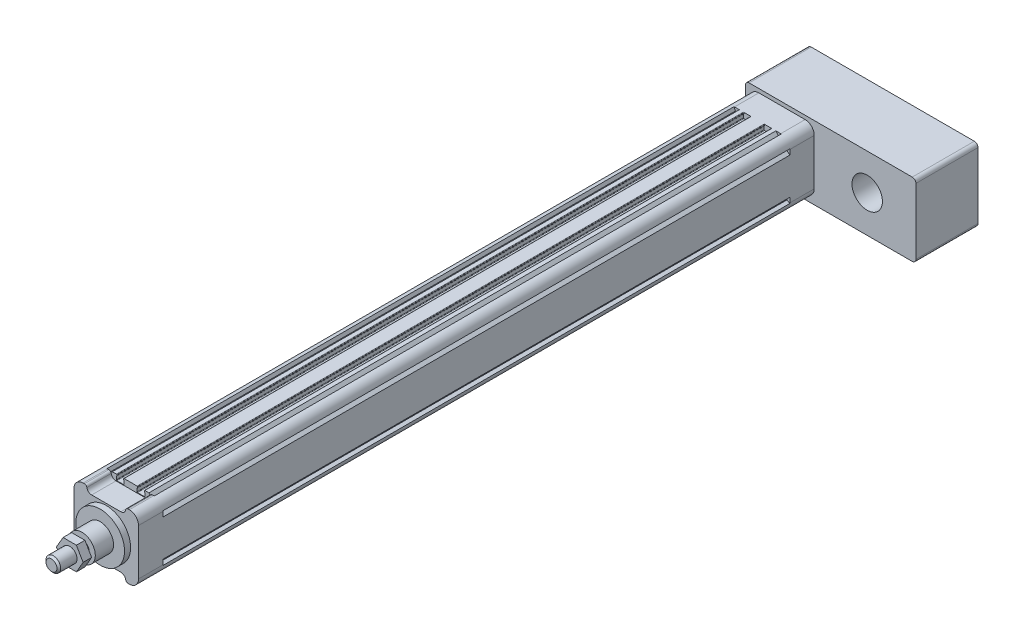
SolidWorks part; units mm, degrees
ref_plane "Front" through (0, 0, 0) normal (0, 0, 1) x (1, 0, 0)
ref_plane "Top" through (0, 0, 0) normal (0, 1, 0) x (1, 0, 0)
ref_plane "Right" through (0, 0, 0) normal (1, 0, 0) x (0, 0, -1)
sketch "草图1" plane through (0, 0, 0) normal (0, 0, 1) x (1, 0, 0)
  line L0 (19.7737, 3) -> (23.3, 3)
  line L1 (23.3, 3) -> (23.3, -3)
  line L2 (23.3, -3) -> (19.7737, -3)
  line L3 (-19.7737, -3) -> (-23.3, -3)
  line L4 (-23.3, -3) -> (-23.3, 3)
  line L5 (-23.3, 3) -> (-19.7737, 3)
  line L6 (-18.2, 24) -> (-19.4434, 26.4869)
  line L7 (-26.4869, 19.4434) -> (-24, 18.2)
  line L8 (-24, 18.2) -> (-24, 17.1)
  line L9 (-24, 17.1) -> (-26.5, 15)
  line L10 (-26.5, 15) -> (-26.5, -15)
  line L11 (-26.5, -15) -> (-24, -17.1)
  line L12 (-24, -17.1) -> (-24, -18.2)
  line L13 (-24, -18.2) -> (-26.4869, -19.4434)
  line L14 (-19.4434, -26.4869) -> (-18.2, -24)
  line L15 (-18.2, -24) -> (-17.1, -24)
  line L16 (-17.1, -24) -> (-15, -26.5)
  line L17 (-15, -26.5) -> (-11.65, -26.5)
  line L18 (-11.25, -26.1) -> (-11.25, -25.6)
  line L19 (-11.65, -25.2) -> (-11.75, -25.2)
  line L20 (-11.75, -25.2) -> (-11.75, -22.4)
  line L21 (-11.35, -22) -> (-5.65, -22)
  line L22 (-5.25, -22.4) -> (-5.25, -25.2)
  line L23 (-5.25, -25.2) -> (-5.35, -25.2)
  line L24 (-5.75, -25.6) -> (-5.75, -26.1)
  line L25 (-5.35, -26.5) -> (5.35, -26.5)
  line L26 (5.75, -26.1) -> (5.75, -25.6)
  line L27 (5.35, -25.2) -> (5.25, -25.2)
  line L28 (5.25, -25.2) -> (5.25, -22.4)
  line L29 (5.65, -22) -> (11.35, -22)
  line L30 (11.75, -22.4) -> (11.75, -25.2)
  line L31 (11.75, -25.2) -> (11.65, -25.2)
  line L32 (11.25, -25.6) -> (11.25, -26.1)
  line L33 (11.65, -26.5) -> (15, -26.5)
  line L34 (15, -26.5) -> (17.1, -24)
  line L35 (17.1, -24) -> (18.2, -24)
  line L36 (18.2, -24) -> (19.4434, -26.4869)
  line L37 (26.4869, -19.4434) -> (24, -18.2)
  line L38 (24, -18.2) -> (24, -17.1)
  line L39 (24, -17.1) -> (26.5, -15)
  line L40 (26.5, -15) -> (26.5, 15)
  line L41 (26.5, 15) -> (24, 17.1)
  line L42 (24, 17.1) -> (24, 18.2)
  line L43 (24, 18.2) -> (26.4869, 19.4434)
  line L44 (19.4434, 26.4869) -> (18.2, 24)
  line L45 (18.2, 24) -> (17.1, 24)
  line L46 (17.1, 24) -> (15, 26.5)
  line L47 (15, 26.5) -> (11.65, 26.5)
  line L48 (11.25, 26.1) -> (11.25, 25.6)
  line L49 (11.65, 25.2) -> (11.75, 25.2)
  line L50 (11.75, 25.2) -> (11.75, 22.4)
  line L51 (11.35, 22) -> (5.65, 22)
  line L52 (5.25, 22.4) -> (5.25, 25.2)
  line L53 (5.25, 25.2) -> (5.35, 25.2)
  line L54 (5.75, 25.6) -> (5.75, 26.1)
  line L55 (5.35, 26.5) -> (-5.35, 26.5)
  line L56 (-5.75, 26.1) -> (-5.75, 25.6)
  line L57 (-5.35, 25.2) -> (-5.25, 25.2)
  line L58 (-5.25, 25.2) -> (-5.25, 22.4)
  line L59 (-5.65, 22) -> (-11.35, 22)
  line L60 (-11.75, 22.4) -> (-11.75, 25.2)
  line L61 (-11.75, 25.2) -> (-11.65, 25.2)
  line L62 (-11.25, 25.6) -> (-11.25, 26.1)
  line L63 (-11.65, 26.5) -> (-15, 26.5)
  line L64 (-15, 26.5) -> (-17.1, 24)
  line L65 (-17.1, 24) -> (-18.2, 24)
  arc A0 (19.7737, 3) -> (-19.7737, 3) centre (0, 0) ccw
  arc A1 (-19.7737, -3) -> (19.7737, -3) centre (0, 0) ccw
  circle A2 centre (19, 19) radius 2.1
  circle A3 centre (19, -19) radius 2.1
  circle A4 centre (-19, -19) radius 2.1
  circle A5 centre (-19, 19) radius 2.1
  arc A6 (-19.4434, 26.4869) -> (-26.4869, 19.4434) centre (-19, 19) ccw
  arc A7 (-26.4869, -19.4434) -> (-19.4434, -26.4869) centre (-19, -19) ccw
  arc A8 (-11.65, -26.5) -> (-11.25, -26.1) centre (-11.65, -26.1) ccw
  arc A9 (-11.25, -25.6) -> (-11.65, -25.2) centre (-11.65, -25.6) ccw
  arc A10 (-11.35, -22) -> (-11.75, -22.4) centre (-11.35, -22.4) ccw
  arc A11 (-5.25, -22.4) -> (-5.65, -22) centre (-5.65, -22.4) ccw
  arc A12 (-5.35, -25.2) -> (-5.75, -25.6) centre (-5.35, -25.6) ccw
  arc A13 (-5.75, -26.1) -> (-5.35, -26.5) centre (-5.35, -26.1) ccw
  arc A14 (5.35, -26.5) -> (5.75, -26.1) centre (5.35, -26.1) ccw
  arc A15 (5.75, -25.6) -> (5.35, -25.2) centre (5.35, -25.6) ccw
  arc A16 (5.65, -22) -> (5.25, -22.4) centre (5.65, -22.4) ccw
  arc A17 (11.75, -22.4) -> (11.35, -22) centre (11.35, -22.4) ccw
  arc A18 (11.65, -25.2) -> (11.25, -25.6) centre (11.65, -25.6) ccw
  arc A19 (11.25, -26.1) -> (11.65, -26.5) centre (11.65, -26.1) ccw
  arc A20 (19.4434, -26.4869) -> (26.4869, -19.4434) centre (19, -19) ccw
  arc A21 (26.4869, 19.4434) -> (19.4434, 26.4869) centre (19, 19) ccw
  arc A22 (11.65, 26.5) -> (11.25, 26.1) centre (11.65, 26.1) ccw
  arc A23 (11.25, 25.6) -> (11.65, 25.2) centre (11.65, 25.6) ccw
  arc A24 (11.35, 22) -> (11.75, 22.4) centre (11.35, 22.4) ccw
  arc A25 (5.25, 22.4) -> (5.65, 22) centre (5.65, 22.4) ccw
  arc A26 (5.35, 25.2) -> (5.75, 25.6) centre (5.35, 25.6) ccw
  arc A27 (5.75, 26.1) -> (5.35, 26.5) centre (5.35, 26.1) ccw
  arc A28 (-5.35, 26.5) -> (-5.75, 26.1) centre (-5.35, 26.1) ccw
  arc A29 (-5.75, 25.6) -> (-5.35, 25.2) centre (-5.35, 25.6) ccw
  arc A30 (-5.65, 22) -> (-5.25, 22.4) centre (-5.65, 22.4) ccw
  arc A31 (-11.75, 22.4) -> (-11.35, 22) centre (-11.35, 22.4) ccw
  arc A32 (-11.65, 25.2) -> (-11.25, 25.6) centre (-11.65, 25.6) ccw
  arc A33 (-11.25, 26.1) -> (-11.65, 26.5) centre (-11.65, 26.1) ccw
extrude "凸台-拉伸1" add sketch "草图1" along normal blind 515
sketch "草图6" plane through (0, 0, 515) normal (0, 0, 1) x (1, 0, 0)
  line L0 (0, 0) -> (19, 0) construction
  line L2 (-26.5, -19) -> (-26.5, 19)
  line L3 (-19, 26.5) -> (-17.9161, 26.5)
  line L4 (26.5, -19) -> (26.5, 19)
  line L5 (-26.5, -26.5) -> (26.5, 26.5) construction
  line L6 (-26.5, 26.5) -> (26.5, -26.5) construction
  line L7 (-12, 21.5) -> (12, 21.5)
  line L9 (19, 26.5) -> (17.9161, 26.5)
  line L10 (19, -26.5) -> (17.9161, -26.5)
  line L11 (-12, -21.5) -> (12, -21.5)
  line L12 (-19, -26.5) -> (-17.9161, -26.5)
  arc A0 (12, 21.5) -> (15.9441, 24.8333) centre (12, 25.5) ccw
  arc A1 (-15.9441, 24.8333) -> (-12, 21.5) centre (-12, 25.5) ccw
  arc A2 (-15.9441, 24.8333) -> (-17.9161, 26.5) centre (-17.9161, 24.5) ccw
  arc A3 (15.9441, 24.8333) -> (17.9161, 26.5) centre (17.9161, 24.5) cw
  arc A4 (-26.5, -19) -> (-19, -26.5) centre (-19, -19) ccw
  arc A5 (19, -26.5) -> (26.5, -19) centre (19, -19) ccw
  arc A6 (26.5, 19) -> (19, 26.5) centre (19, 19) ccw
  arc A7 (-26.5, 19) -> (-19, 26.5) centre (-19, 19) cw
  arc A8 (15.9441, -24.8333) -> (17.9161, -26.5) centre (17.9161, -24.5) ccw
  arc A9 (12, -21.5) -> (15.9441, -24.8333) centre (12, -25.5) cw
  arc A10 (-15.9441, -24.8333) -> (-12, -21.5) centre (-12, -25.5) cw
  arc A11 (-15.9441, -24.8333) -> (-17.9161, -26.5) centre (-17.9161, -24.5) cw
  point P0 (0, 0)
  point P9 (0, 21.5)
  point P13 (20, 20.8461)
  point P16 (-12, 20.8461)
  dimension "D5" = 4
  dimension "D6" = 2
  dimension "D7" = 2
  dimension "D9" = 7.5
  dimension "D1" = 53
  dimension "D2" = 53
  dimension "D3" = 26.5
  dimension "D4" = 24
  dimension "D8" = 5
extrude "凸台-拉伸2" add sketch "草图6" along normal blind 20
sketch "草图7" plane through (0, 0, 535) normal (0, 0, 1) x (1, 0, 0)
  circle A0 centre (0, 0) radius 20
  dimension "D1" = 40
extrude "凸台-拉伸3" add sketch "草图7" along normal blind 5
sketch "草图9" plane through (0, 0, 540) normal (0, 0, 1) x (1, 0, 0)
  circle A0 centre (0, 0) radius 11
  dimension "D1" = 22
extrude "凸台-拉伸4" add sketch "草图9" along normal blind 15
sketch "草图10" plane through (0, 0, 555) normal (0, 0, 1) x (1, 0, 0)
  circle A0 centre (0, 0) radius 6
  dimension "D1" = 12
extrude "凸台-拉伸5" add sketch "草图10" along normal blind 25
sketch "草图11" plane through (0, 0, 0) normal (0, 0, -1) x (-1, 0, 0)
  line L1 (-19, -26.5) -> (19, -26.5)
  line L2 (-26.5, -19) -> (-26.5, 19)
  line L3 (-19, 26.5) -> (19, 26.5)
  line L4 (26.5, -19) -> (26.5, 19)
  line L5 (-26.5, -26.5) -> (26.5, 26.5) construction
  line L6 (-26.5, 26.5) -> (26.5, -26.5) construction
  arc A0 (-26.5, -19) -> (-19, -26.5) centre (-19, -19) ccw
  arc A1 (19, -26.5) -> (26.5, -19) centre (19, -19) ccw
  arc A2 (26.5, 19) -> (19, 26.5) centre (19, 19) ccw
  arc A3 (-26.5, 19) -> (-19, 26.5) centre (-19, 19) cw
  point P0 (0, 0)
  dimension "D3" = 7.5
  dimension "D1" = 53
  dimension "D2" = 53
extrude "凸台-拉伸6" add sketch "草图11" along normal blind 20
sketch "草图12" plane through (0, 0, -20) normal (0, 0, -1) x (-1, 0, 0)
  line L1 (-107, -30.4042) -> (27, -30.4042)
  line L2 (-110, -27.4042) -> (-110, 26.5958)
  line L3 (-107, 29.5958) -> (27, 29.5958)
  line L4 (30, -27.4042) -> (30, 26.5958)
  line L5 (-110, -30.4042) -> (30, 29.5958) construction
  line L6 (-110, 29.5958) -> (30, -30.4042) construction
  arc A0 (27, 29.5958) -> (30, 26.5958) centre (27, 26.5958) cw
  arc A1 (30, -27.4042) -> (27, -30.4042) centre (27, -27.4042) cw
  arc A2 (-110, -27.4042) -> (-107, -30.4042) centre (-107, -27.4042) ccw
  arc A3 (-110, 26.5958) -> (-107, 29.5958) centre (-107, 26.5958) cw
  point P0 (-40, -0.4042)
  dimension "D4" = 3
  dimension "D1" = 60
  dimension "D2" = 140
  dimension "D3" = 30
extrude "凸台-拉伸7" add sketch "草图12" along normal blind 51
sketch "草图13" plane through (0, 0, -20) normal (0, 0, 1) x (1, 0, 0)
  circle A0 centre (70, 0) radius 12.5
  dimension "D2" = 25
  dimension "D1" = 70
extrude "切除-拉伸2" cut sketch "草图13" against normal blind 30
hole_wizard "M6 螺纹孔1" positions "草图14" profile "草图15" tap size "M6" standard "GB"
sketch "草图14" plane through (0, 0, -71) normal (0, 0, -1) x (-1, 0, 0)
  line L0 (30, -27.4042) -> (30, 26.5958) construction
  point P0 (19, -19)
  dimension "D1" = 11
  dimension "D2" = 19
sketch "草图15" plane through (-19, -19, -71) normal (1, 0, 0) x (0, 1, 0)
  line L0 (0, 0) -> (0, 16.5022)
  line L1 (0, 16.5022) -> (2.5, 15)
  line L2 (2.5, 15) -> (2.5, 0)
  line L5 (2.5, 0) -> (0, 0)
  line L10 (0, 16.5022) -> (-2.5, 15) construction
  line L11 (0, -6.35) -> (0, 107.95) construction
  dimension "螺纹孔钻头直径" = 5
  dimension "螺纹孔钻头深度" = 15
  dimension "导头角度" = 118
cosmetic thread "孔螺蚊线4" parameters "D1"=12, "D2"=6
pattern_linear "阵列(线性)1" count 2 spacing 38 along (0, 1, 0) count 2 spacing 38 along (1, 0, 0) of "M6 螺纹孔1"
hole_wizard "M6 螺纹孔2" positions "草图16" profile "草图17" tap size "M6" standard "GB"
sketch "草图16" plane through (0, 0, -71) normal (0, 0, -1) x (-1, 0, 0)
  circle A1 centre (-19, 19) radius 2.5 construction
  circle A2 centre (-19, -19) radius 2.5 construction
  point P0 (-84, -19)
  point P2 (-84, 19)
  dimension "D3" = 65
  dimension "D1" = 19
  dimension "D2" = 19
  dimension "D4" = 65
sketch "草图17" plane through (84, -19, -71) normal (1, 0, 0) x (0, 1, 0)
  line L0 (0, 0) -> (0, 16.5022)
  line L1 (0, 16.5022) -> (2.5, 15)
  line L2 (2.5, 15) -> (2.5, 0)
  line L5 (2.5, 0) -> (0, 0)
  line L10 (0, 16.5022) -> (-2.5, 15) construction
  line L11 (0, -6.35) -> (0, 107.95) construction
  dimension "螺纹孔钻头直径" = 5
  dimension "螺纹孔钻头深度" = 15
  dimension "导头角度" = 118
cosmetic thread "孔螺蚊线5" parameters "D1"=12, "D2"=6
cosmetic thread "孔螺蚊线6" parameters "D1"=12, "D2"=6
hole_wizard "M6 螺纹孔3" positions "草图19" profile "草图20" tap size "M6" standard "GB"
sketch "草图19" plane through (-26.5, 0, 0) normal (-1, 0, 0) x (0, 0, 1)
  line L0 (535, 19) -> (535, -19) construction
  point P0 (525, 11)
  point P2 (525, -11)
  dimension "D1" = 10
  dimension "D2" = 10
  dimension "D3" = 22
  dimension "D4" = 11
sketch "草图20" plane through (-26.5, 11, 525) normal (0, 1, 0) x (0, 0, 1)
  line L0 (0, 0) -> (0, 16.5022)
  line L1 (0, 16.5022) -> (2.5, 15)
  line L2 (2.5, 15) -> (2.5, 0)
  line L5 (2.5, 0) -> (0, 0)
  line L10 (0, 16.5022) -> (-2.5, 15) construction
  line L11 (0, -6.35) -> (0, 107.95) construction
  dimension "螺纹孔钻头直径" = 5
  dimension "螺纹孔钻头深度" = 15
  dimension "导头角度" = 118
cosmetic thread "孔螺蚊线7" parameters "D1"=12, "D2"=6
cosmetic thread "孔螺蚊线8" parameters "D1"=12, "D2"=6
hole_wizard "M6 螺纹孔4" positions "草图21" profile "草图22" tap size "M6" standard "GB"
sketch "草图21" plane through (-26.5, 0, 0) normal (-1, 0, 0) x (0, 0, 1)
  line L0 (-20, -27.4042) -> (-20, 26.5958) construction
  line L1 (-20, -19) -> (-20, 19) construction
  point P0 (-10, 11)
  point P2 (-10, -11)
  dimension "D1" = 10
  dimension "D2" = 10
  dimension "D3" = 11
  dimension "D4" = 11
sketch "草图22" plane through (-26.5, 11, -10) normal (0, 1, 0) x (0, 0, 1)
  line L0 (0, 0) -> (0, 16.5022)
  line L1 (0, 16.5022) -> (2.5, 15)
  line L2 (2.5, 15) -> (2.5, 0)
  line L5 (2.5, 0) -> (0, 0)
  line L10 (0, 16.5022) -> (-2.5, 15) construction
  line L11 (0, -6.35) -> (0, 107.95) construction
  dimension "螺纹孔钻头直径" = 5
  dimension "螺纹孔钻头深度" = 15
  dimension "导头角度" = 118
cosmetic thread "孔螺蚊线9" parameters "D1"=12, "D2"=6
cosmetic thread "孔螺蚊线10" parameters "D1"=12, "D2"=6
chamfer "倒角1" distance 1.5 angle 45 1 edges at (6, 0, 580)
sketch "草图23" plane through (0, 0, 555) normal (0, 0, 1) x (1, 0, 0)
  line L1 (10.9697, 0) -> (5.4848, 9.5)
  line L2 (5.4848, 9.5) -> (-5.4848, 9.5)
  line L3 (-5.4848, 9.5) -> (-10.9697, 0)
  line L4 (-10.9697, 0) -> (-5.4848, -9.5)
  line L5 (-5.4848, -9.5) -> (5.4848, -9.5)
  line L6 (5.4848, -9.5) -> (10.9697, 0)
  circle A0 centre (0, 0) radius 9.5 construction
  dimension "D1" = 19
extrude "凸台-拉伸8" add sketch "草图23" along normal blind 7 from offset 3
